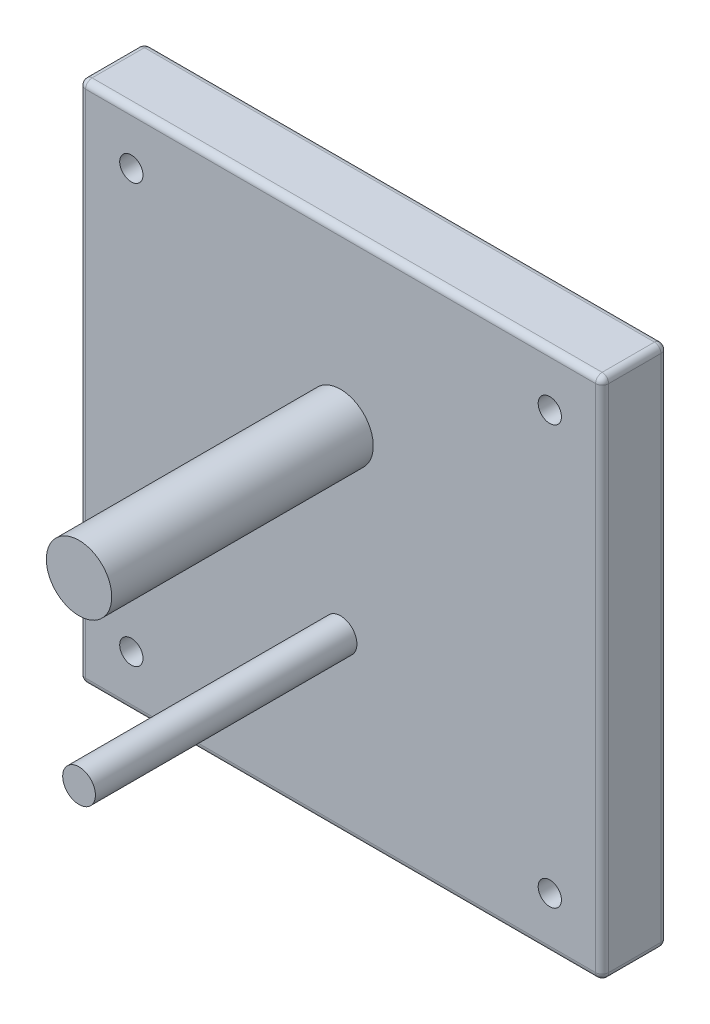
SolidWorks part; units mm, degrees
ref_plane "Front Plane" through (0, 0, 0) normal (1, 0, 0) x (0, 1, 0)
ref_plane "Top Plane" through (0, 0, 0) normal (0, 0, 1) x (0, 1, 0)
ref_plane "Right Plane" through (0, 0, 0) normal (0, 1, 0) x (-1, 0, 0)
sketch "Sketch1" plane through (0, 0, 0) normal (0, 0, 1) x (0, 1, 0)
  line L1 (-25.4, -25.4) -> (25.4, -25.4)
  line L2 (-25.4, -25.4) -> (-25.4, 25.4)
  line L3 (-25.4, 25.4) -> (25.4, 25.4)
  line L4 (25.4, -25.4) -> (25.4, 25.4)
  line L5 (-25.4, -25.4) -> (25.4, 25.4) construction
  line L6 (-25.4, 25.4) -> (25.4, -25.4) construction
  point P0 (0, 0)
  dimension "D1" = 50.8
extrude "Boss-Extrude1" add sketch "Sketch1" along normal blind 6.35
sketch "Sketch2" plane through (0, 0, 6.35) normal (0, 0, 1) x (1, 0, 0)
  line L0 (-25.4, 0) -> (25.4, 0) construction
  line L1 (-25.4, 25.4) -> (-25.4, -25.4) construction
  line L2 (25.4, -25.4) -> (25.4, 25.4) construction
  line L3 (0, -25.4) -> (0, 25.4) construction
  line L4 (-25.4, -25.4) -> (25.4, -25.4) construction
  line L5 (25.4, 25.4) -> (-25.4, 25.4) construction
  circle A0 centre (0, -8.7312) radius 1.5875
  circle A1 centre (0, 8.7312) radius 3.175
  dimension "D1" = 3.175
  dimension "D2" = 6.35
  dimension "D3" = 8.7312
  dimension "D4" = 8.7312
extrude "Boss-Extrude2" add sketch "Sketch2" along normal blind 25.4
hole_wizard "#4-40 Tapped Hole1" positions "Sketch3" profile "Sketch4" tap size "#4-40" standard "ANSI Inch" end condition through all
sketch "Sketch3" plane through (0, 0, 6.35) normal (0, 0, 1) x (1, 0, 0)
  line L0 (-25.4, 0) -> (25.4, 0) construction
  line L1 (-25.4, 25.4) -> (-25.4, -25.4) construction
  line L2 (25.4, -25.4) -> (25.4, 25.4) construction
  line L5 (0, 25.4) -> (0, -25.4) construction
  line L6 (25.4, 25.4) -> (-25.4, 25.4) construction
  line L7 (-25.4, -25.4) -> (25.4, -25.4) construction
  line L10 (-20.32, 20.32) -> (20.32, 20.32) construction
  line L11 (20.32, 20.32) -> (20.32, -20.32) construction
  line L12 (20.32, -20.32) -> (-20.32, -20.32) construction
  line L13 (-20.32, -20.32) -> (-20.32, 20.32) construction
  point P20 (-20.32, 20.32)
  point P22 (20.32, 20.32)
  point P24 (20.32, -20.32)
  point P26 (-20.32, -20.32)
  dimension "D1" = 20.32
  dimension "D2" = 20.32
  dimension "D3" = 20.32
  dimension "D4" = 20.32
sketch "Sketch4" plane through (-20.32, -20.32, 6.35) normal (1, 0, 0) x (0, -1, 0)
  line L0 (0, 0) -> (0, 6.35)
  line L1 (0, 6.35) -> (1.1303, 6.35)
  line L2 (1.1303, 6.35) -> (1.1303, 0)
  line L5 (1.1303, 0) -> (0, 0)
  line L11 (0, -6.35) -> (0, 107.95) construction
  dimension "Thru Tap Drill Dia." = 2.2606
  dimension "Thru Tap Drill Depth" = 6.35
fillet "Fillet1" radius 0.635 12 edges at (25.4, 0, 6.35) (25.4, 0, 0) (25.4, 25.4, 3.175) (0, 25.4, 6.35) (0, 25.4, 0) (-25.4, 25.4, 3.175) (-25.4, 0, 6.35) (-25.4, 0, 0) (-25.4, -25.4, 3.175) (0, -25.4, 6.35) (25.4, -25.4, 3.175) (0, -25.4, 0)
equation "\"N_pinion\"= 18"
equation "\"N_gear\"= 48"
equation "\"DP\"= 48"
equation "\"d_pinion\"= \"N_pinion\" / \"DP\""
equation "\"d_gear\"= \"N_gear\" / \"DP\""
equation "\"CD\"= ( \"d_pinion\" + \"d_gear\" ) / 2"
equation "\"bearing_L\"= 0.25"
equation "\"plate_t\"= \"bearing_L\""
equation "\"shaft_L\"= 1"
equation "\"cavity\"= \"shaft_L\" - 2 * \"plate_t\""
equation "\"plate_w\"= 2"
equation "\"screw_off\"= 0.2"
equation "\"bore_pinion\"= 0.25"
equation "\"bore_gear\"= 0.375"
equation "\"D_shaft_pinion\"= 0.125"
equation "\"D1@Sketch1\"=\"plate_w\""
equation "\"D1@Boss-Extrude1\"=\"plate_t\""
equation "\"D1@Sketch2\"=\"D_shaft_pinion\""
equation "\"D2@Sketch2\"=\"bore_pinion\""
equation "\"D3@Sketch2\"=\"CD\"/2"
equation "\"D4@Sketch2\"=\"CD\"/2"
equation "\"D1@Sketch3\"=\"plate_w\" / 2 - \"screw_off\""
equation "\"D2@Sketch3\"=\"plate_w\" / 2 - \"screw_off\""
equation "\"D3@Sketch3\"=\"plate_w\" / 2 - \"screw_off\""
equation "\"D4@Sketch3\"=\"plate_w\" / 2 - \"screw_off\""
